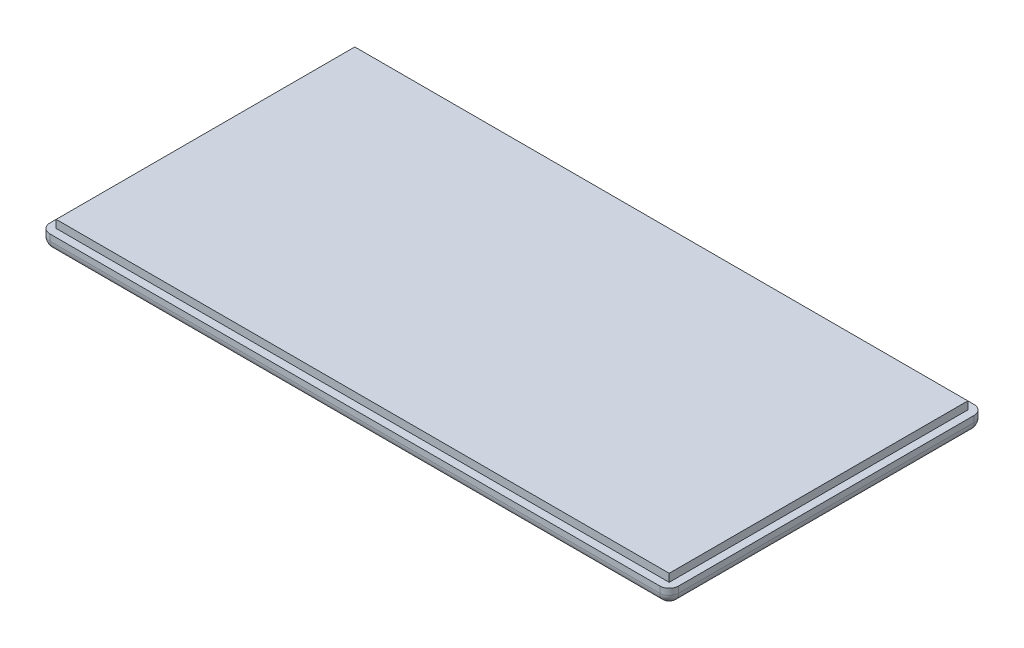
SolidWorks part; units mm, degrees
ref_plane "Front Plane" through (0, 0, 0) normal (0, 0, 1) x (1, 0, 0)
ref_plane "Top Plane" through (0, 0, 0) normal (0, 1, 0) x (1, 0, 0)
ref_plane "Right Plane" through (0, 0, 0) normal (1, 0, 0) x (0, 0, -1)
sketch "Sketch1" plane through (0, 0, 0) normal (0, 1, 0) x (1, 0, 0)
  line L1 (0, 0) -> (200, 0)
  line L2 (0, 0) -> (0, -100)
  line L3 (0, -100) -> (200, -100)
  line L4 (200, 0) -> (200, -100)
  dimension "D1" = 200
  dimension "D2" = 100
extrude "Boss-Extrude1" add sketch "Sketch1" along normal blind 5
sketch "Sketch2" plane through (0, 5, 0) normal (0, 1, 0) x (1, 0, 0)
  line L13 (2.5, -2.5) -> (197.5, -2.5)
  line L14 (2.5, -2.5) -> (2.5, -97.5)
  line L15 (2.5, -97.5) -> (197.5, -97.5)
  line L16 (197.5, -2.5) -> (197.5, -97.5)
extrude "Boss-Extrude2" add sketch "Sketch2" along normal blind 2.5
fillet "Fillet1" radius 3 4 edges at (200, 2.5, 100) (200, 2.5, 0) (0, 2.5, 0) (0, 2.5, 100)
fillet "Fillet2" radius 3 8 edges at (199.1213, 0, 99.1213) (100, 0, 100) (0.8787, 0, 99.1213) (0, 0, 50) (0.8787, 0, 0.8787) (100, 0, 0) (199.1213, 0, 0.8787) (200, 0, 50)
